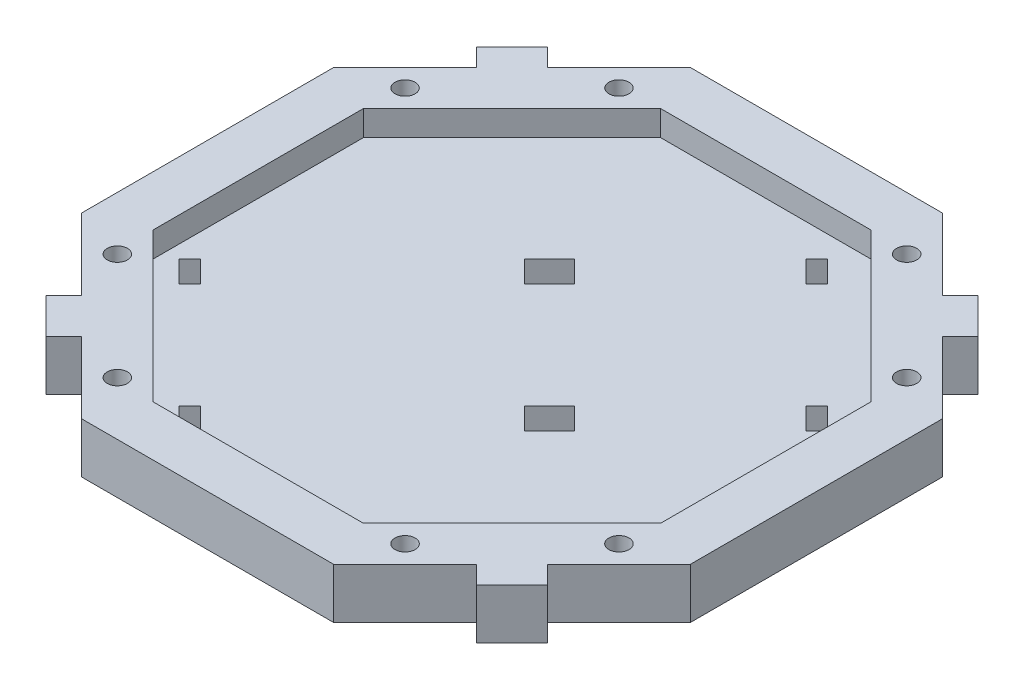
SolidWorks part; units mm, degrees
ref_plane "Plan de face" through (0, 0, 0) normal (0, 0, 1) x (1, 0, 0)
ref_plane "Plan de dessus" through (0, 0, 0) normal (0, 1, 0) x (1, 0, 0)
ref_plane "Plan de droite" through (0, 0, 0) normal (1, 0, 0) x (0, 0, -1)
sketch "Esquisse1" plane through (0, 0, 0) normal (0, 1, 0) x (1, 0, 0)
  line L8 (60.3553, 25) -> (25, 60.3553)
  line L9 (-25, 60.3553) -> (-60.3553, 25)
  line L10 (-60.3553, 25) -> (-60.3553, -25)
  line L11 (-60.3553, -25) -> (-25, -60.3553)
  line L12 (-25, -60.3553) -> (25, -60.3553)
  line L13 (25, -60.3553) -> (60.3553, -25)
  line L14 (60.3553, -25) -> (60.3553, 25)
  line L15 (25, 60.3553) -> (-25, 60.3553)
  line L16 (-46.2132, 39.1421) -> (-49.7487, 42.6777)
  line L17 (-49.7487, 42.6777) -> (-42.6777, 49.7487)
  line L18 (-42.6777, 49.7487) -> (-39.1421, 46.2132)
  line L19 (-42.6777, 42.6777) -> (-46.2132, 46.2132) construction
  line L20 (-55, 0) -> (55, 0) construction
  line L21 (-46.2132, -39.1421) -> (-49.7487, -42.6777)
  line L22 (-49.7487, -42.6777) -> (-42.6777, -49.7487)
  line L23 (-42.6777, -49.7487) -> (-39.1421, -46.2132)
  line L24 (0, -55) -> (0, 55) construction
  line L25 (42.6777, 49.7487) -> (39.1421, 46.2132)
  line L26 (49.7487, 42.6777) -> (42.6777, 49.7487)
  line L27 (46.2132, 39.1421) -> (49.7487, 42.6777)
  line L28 (46.2132, -39.1421) -> (49.7487, -42.6777)
  line L29 (49.7487, -42.6777) -> (42.6777, -49.7487)
  line L30 (42.6777, -49.7487) -> (39.1421, -46.2132)
  circle A0 centre (0, 0) radius 60.3553 construction
  point P12 (0, 60.3553)
  dimension "D1" = 50
  dimension "D2" = 10
  dimension "D3" = 5
extrude "Boss.-Extru.2" add sketch "Esquisse1" along normal blind 10 contours L8 L15 L9 L10 L11 L12 L13 L14 | L8 L27 L26 L25 | L30 L29 L28 L13 | L22 L23 L11 L21 | L18 L17 L16 L9
sketch "Esquisse3" plane through (0, 0, 0) normal (0, 1, 0) x (1, 0, 0)
  line L7 (-46.2132, 39.1421) -> (-49.7487, 42.6777) construction
  line L8 (-42.6777, 49.7487) -> (-39.1421, 46.2132) construction
  line L9 (-46.2132, 39.1421) -> (-60.3553, 25) construction
  line L10 (-25, 60.3553) -> (-39.1421, 46.2132) construction
  line L11 (0, -5.5) -> (0, 5.5) construction
  line L12 (-5.5, 0) -> (5.5, 0) construction
  point P0 (-49.7487, 28.5355)
  point P1 (-28.5355, 49.7487)
  point P12 (28.5355, 49.7487)
  point P13 (49.7487, 28.5355)
  point P16 (49.7487, -28.5355)
  point P17 (28.5355, -49.7487)
  point P18 (-28.5355, -49.7487)
  point P19 (-49.7487, -28.5355)
  dimension "D1" = 10
  dimension "D2" = 10
  dimension "D3" = 5
  dimension "D4" = 5
hole_wizard "Chambrage pour tête cylindrique fendue M31" positions "Esquisse3D1" profile "Esquisse5" counterbore size "M3" standard "ISO" end condition through all
sketch3d "Esquisse3D1"
  point P0 (-49.7487, 0, -28.5355)
  point P3 (-28.5355, 0, -49.7487)
  point P6 (28.5355, 0, -49.7487)
  point P9 (49.7487, 0, -28.5355)
  point P12 (28.5355, 0, 49.7487)
  point P15 (49.7487, 0, 28.5355)
  point P18 (-28.5355, 0, 49.7487)
  point P21 (-49.7487, 0, 28.5355)
sketch "Esquisse5" plane through (-49.7487, 0, -28.5355) normal (1, 0, 0) x (0, 0, -1)
  line L0 (0, 0) -> (0, 10)
  line L1 (0, 10) -> (2, 10)
  line L3 (2, 10) -> (2, 4)
  line L4 (2, 4) -> (2.75, 4)
  line L5 (2.75, 4) -> (2.75, 0)
  line L7 (2.75, 0) -> (0, 0)
  line L11 (0, -6.35) -> (0, 107.95) construction
  dimension "Diamètre du perçage jusqu'au prochain" = 4
  dimension "Profondeur du perçage jusqu'au prochain" = 10
  dimension "Diamètre du chambrage" = 5.5
  dimension "Profondeur du chambrage" = 4
sketch "Esquisse6" plane through (0, 10, 0) normal (0, 1, 0) x (1, 0, 0)
  line L0 (25, 60.3553) -> (-25, 60.3553) construction
  line L1 (20.8579, 50.3553) -> (-20.8579, 50.3553)
  line L2 (-20.8579, 50.3553) -> (-50.3553, 20.8579)
  line L3 (-50.3553, 20.8579) -> (-50.3553, -20.8579)
  line L4 (-50.3553, -20.8579) -> (-20.8579, -50.3553)
  line L5 (-20.8579, -50.3553) -> (20.8579, -50.3553)
  line L6 (20.8579, -50.3553) -> (50.3553, -20.8579)
  line L7 (50.3553, -20.8579) -> (50.3553, 20.8579)
  line L8 (50.3553, 20.8579) -> (20.8579, 50.3553)
  circle A0 centre (0, 0) radius 50.3553 construction
  dimension "D1" = 10
extrude "Enlèv. mat.-Extru.1" cut sketch "Esquisse6" against normal blind 5
sketch "Esquisse7" plane through (0, 5, 0) normal (0, 1, 0) x (1, 0, 0)
  line L0 (-47.78, -18.2825) -> (-45.6586, -16.1612)
  line L1 (-45.6586, -16.1612) -> (-41.416, -20.4038)
  line L2 (-41.416, -20.4038) -> (-43.5373, -22.5251)
  line L3 (-43.5373, -22.5251) -> (-47.78, -18.2825)
  line L4 (-13.4853, 16.0122) -> (-8.5355, 20.9619)
  line L5 (-8.5355, 20.9619) -> (-4.2929, 16.7193)
  line L6 (-4.2929, 16.7193) -> (-9.2426, 11.7696)
  line L7 (-9.2426, 11.7696) -> (-13.4853, 16.0122)
  line L8 (14.3934, 43.8909) -> (16.5147, 46.0122)
  line L9 (16.5147, 46.0122) -> (20.7574, 41.7696)
  line L10 (20.7574, 41.7696) -> (18.636, 39.6482)
  line L11 (18.636, 39.6482) -> (14.3934, 43.8909)
  line L12 (49.7487, -42.6777) -> (42.6777, -49.7487) construction
  line L17 (-22.0711, 20.3553) -> (20.3553, -22.0711) construction
  line L20 (50.3553, 4.3934) -> (4.3934, 50.3553) construction
  line L21 (-7.9289, -50.3553) -> (-50.3553, -7.9289) construction
  line L23 (-47.78, -18.2825) -> (-50.3553, -20.8579) construction
  line L24 (-50.3553, -20.8579) -> (-20.8579, -50.3553) construction
  line L25 (-50.3553, -20.8579) -> (-20.8579, -50.3553) construction
  line L26 (-35.6066, -35.6066) -> (35.6066, 35.6066) construction
  line L27 (50.3553, 20.8579) -> (20.8579, 50.3553) construction
  line L28 (-20.4038, -41.416) -> (-22.5251, -43.5373)
  line L29 (-16.1612, -45.6586) -> (-20.4038, -41.416)
  line L30 (-18.2825, -47.78) -> (-16.1612, -45.6586)
  line L31 (-22.5251, -43.5373) -> (-18.2825, -47.78)
  line L32 (39.6482, 18.636) -> (43.8909, 14.3934)
  line L33 (41.7696, 20.7574) -> (39.6482, 18.636)
  line L34 (46.0122, 16.5147) -> (41.7696, 20.7574)
  line L35 (43.8909, 14.3934) -> (46.0122, 16.5147)
  line L36 (16.7193, -4.2929) -> (11.7696, -9.2426)
  line L37 (20.9619, -8.5355) -> (16.7193, -4.2929)
  line L38 (16.0122, -13.4853) -> (20.9619, -8.5355)
  line L39 (11.7696, -9.2426) -> (16.0122, -13.4853)
  dimension "D1" = 6
  dimension "D2" = 3
  dimension "D3" = 2.5
  dimension "D4" = 2.5
  dimension "D5" = 7
  dimension "D6" = 3
extrude "Enlèv. mat.-Extru.2" cut sketch "Esquisse7" against normal up to next
